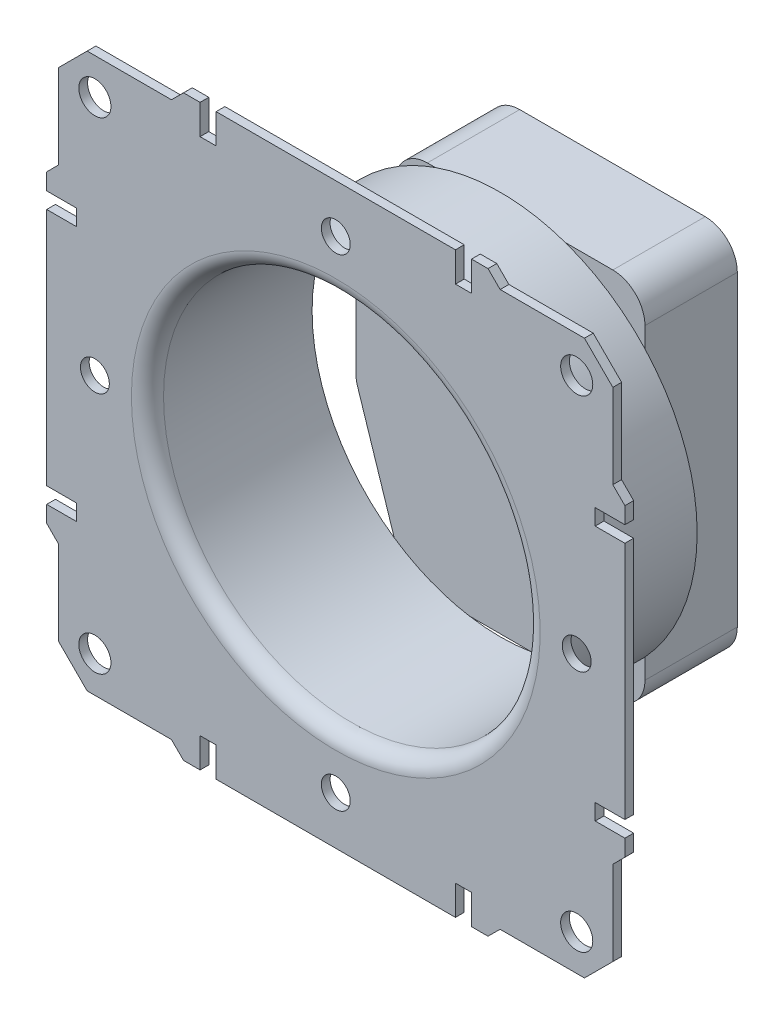
SolidWorks part; units mm, degrees
ref_plane "Спереди" through (0, 0, 0) normal (0, 0, 1) x (1, 0, 0)
ref_plane "Сверху" through (0, 0, 0) normal (0, 1, 0) x (1, 0, 0)
ref_plane "Справа" through (0, 0, 0) normal (1, 0, 0) x (0, 0, -1)
sketch "Эскиз1" plane through (0, 0, 0) normal (0, 0, 1) x (1, 0, 0)
  line L0 (-34.5, -34.5) -> (34.5, 34.5) construction
  line L1 (-34.5, -34.5) -> (34.5, -34.5) construction
  line L2 (-34.5, -34.5) -> (-34.5, 34.5) construction
  line L3 (-34.5, 34.5) -> (34.5, 34.5) construction
  line L4 (34.5, -34.5) -> (34.5, 34.5) construction
  line L5 (-30.9645, 34.5) -> (-34.5, 30.9645)
  line L6 (-34.5, 30.9645) -> (-34.5, 20.4645)
  line L7 (0, 0) -> (-34.5, 0) construction
  line L8 (-34.5, 20.4645) -> (-36, 18.9563)
  line L9 (-36, 18.9563) -> (-36, 16.901)
  line L10 (-36, 16.901) -> (-32.3, 16.901)
  line L11 (-32.3, 16.901) -> (-32.3, 14.901)
  line L12 (-32.3, 14.901) -> (-36, 14.901)
  line L13 (-36, 14.901) -> (-36, -14.901)
  line L14 (-32.3, -14.901) -> (-36, -14.901)
  line L15 (-32.3, -16.901) -> (-32.3, -14.901)
  line L16 (-36, -16.901) -> (-32.3, -16.901)
  line L17 (-36, -18.9563) -> (-36, -16.901)
  line L18 (-34.5, -20.4645) -> (-36, -18.9563)
  line L19 (-34.5, -30.9645) -> (-34.5, -20.4645)
  line L20 (34.5, 30.9645) -> (30.9645, 34.5)
  line L21 (30.9645, 34.5) -> (20.4645, 34.5)
  line L22 (20.4645, 34.5) -> (18.9563, 36)
  line L23 (18.9563, 36) -> (16.901, 36)
  line L24 (16.901, 36) -> (16.901, 32.3)
  line L25 (16.901, 32.3) -> (14.901, 32.3)
  line L26 (14.901, 32.3) -> (14.901, 36)
  line L27 (14.901, 36) -> (-14.901, 36)
  line L28 (-14.901, 32.3) -> (-14.901, 36)
  line L29 (-16.901, 32.3) -> (-14.901, 32.3)
  line L30 (-16.901, 36) -> (-16.901, 32.3)
  line L31 (-18.9563, 36) -> (-16.901, 36)
  line L32 (-20.4645, 34.5) -> (-18.9563, 36)
  line L33 (-30.9645, 34.5) -> (-20.4645, 34.5)
  line L34 (30.9645, -34.5) -> (34.5, -30.9645)
  line L35 (34.5, -30.9645) -> (34.5, -20.4645)
  line L36 (34.5, -20.4645) -> (36, -18.9563)
  line L37 (36, -18.9563) -> (36, -16.901)
  line L38 (36, -16.901) -> (32.3, -16.901)
  line L39 (32.3, -16.901) -> (32.3, -14.901)
  line L40 (32.3, -14.901) -> (36, -14.901)
  line L41 (36, -14.901) -> (36, 14.901)
  line L42 (32.3, 14.901) -> (36, 14.901)
  line L43 (32.3, 16.901) -> (32.3, 14.901)
  line L44 (36, 16.901) -> (32.3, 16.901)
  line L45 (36, 18.9563) -> (36, 16.901)
  line L46 (34.5, 20.4645) -> (36, 18.9563)
  line L47 (34.5, 30.9645) -> (34.5, 20.4645)
  line L48 (-34.5, -30.9645) -> (-30.9645, -34.5)
  line L49 (-30.9645, -34.5) -> (-20.4645, -34.5)
  line L50 (-20.4645, -34.5) -> (-18.9563, -36)
  line L51 (-18.9563, -36) -> (-16.901, -36)
  line L52 (-16.901, -36) -> (-16.901, -32.3)
  line L53 (-16.901, -32.3) -> (-14.901, -32.3)
  line L54 (-14.901, -32.3) -> (-14.901, -36)
  line L55 (-14.901, -36) -> (14.901, -36)
  line L56 (14.901, -32.3) -> (14.901, -36)
  line L57 (16.901, -32.3) -> (14.901, -32.3)
  line L58 (16.901, -36) -> (16.901, -32.3)
  line L59 (18.9563, -36) -> (16.901, -36)
  line L60 (20.4645, -34.5) -> (18.9563, -36)
  line L61 (30.9645, -34.5) -> (20.4645, -34.5)
  circle A0 centre (-30, 30) radius 2
  circle A1 centre (-30, 0) radius 1.8
  circle A2 centre (30, 30) radius 2
  circle A3 centre (0, 30) radius 1.8
  circle A4 centre (30, -30) radius 2
  circle A5 centre (30, 0) radius 1.8
  circle A6 centre (-30, -30) radius 2
  circle A7 centre (0, -30) radius 1.8
  circle A8 centre (0, 0) radius 23.45
  point P5 (0, 0)
  point P21 (-36, 0)
  point P44 (0, 36)
  point P64 (36, 0)
  point P84 (0, -36)
  point P92 (0, 0)
  dimension "D8" = 4
  dimension "D13" = 3.6
  dimension "D16" = 46.9
  dimension "D1" = 69
  dimension "D2" = 69
  dimension "D3" = 5
  dimension "D4" = 45
  dimension "D5" = 10.5
  dimension "D6" = 4.5
  dimension "D7" = 4.5
  dimension "D9" = 1.5
  dimension "D10" = 17.599
  dimension "D11" = 3.7
  dimension "D12" = 2
  dimension "D14" = 6
  dimension "D17" = 72
  dimension "D15" = 4
extrude "Бобышка-Вытянуть1" add sketch "Эскиз1" along normal blind 1.09
sketch "Эскиз2" plane through (0, 0, 1.09) normal (0, 0, 1) x (1, 0, 0)
  circle A0 centre (0, 0) radius 23.45 construction
  circle A1 centre (0, 0) radius 23.45
  circle A2 centre (0, 0) radius 24.5
  dimension "D1" = 49
extrude "Бобышка-Вытянуть2" add sketch "Эскиз2" against normal blind 20.5
fillet "Скругление1" radius 2 2 edges at (23.45, 0, 1.09) (-24.5, 0, 0)
sketch "Эскиз3" plane through (0, 0, -19.41) normal (0, 0, -1) x (-1, 0, 0)
  line L0 (0, -24.5) -> (0, 24.5) construction
  line L1 (-18, -19.125) -> (-18, 19.125)
  line L2 (0, 0) -> (18, 0) construction
  line L3 (18, -4.038) -> (18, 4.038)
  line L4 (17.804, 5.2748) -> (12.8984, 20.3619)
  line L5 (17.804, -5.2748) -> (12.8984, -20.3619)
  line L6 (9.0945, -23.125) -> (-14, -23.125)
  line L7 (-14, 23.125) -> (9.0945, 23.125)
  circle A0 centre (0, 0) radius 24.5 construction
  circle A1 centre (0, 0) radius 24.5 construction
  circle A2 centre (0, 0) radius 1.5
  arc A3 (12.8984, 20.3619) -> (9.0945, 23.125) centre (9.0945, 19.125) ccw
  arc A4 (18, 4.038) -> (17.804, 5.2748) centre (14, 4.038) ccw
  arc A5 (17.804, -5.2748) -> (18, -4.038) centre (14, -4.038) ccw
  arc A6 (12.8984, -20.3619) -> (9.0945, -23.125) centre (9.0945, -19.125) cw
  arc A7 (-14, 23.125) -> (-18, 19.125) centre (-14, 19.125) ccw
  arc A8 (-14, -23.125) -> (-18, -19.125) centre (-14, -19.125) cw
  point P11 (-18, 0)
  point P16 (18, 0)
  point P20 (12, 23.125)
  point P23 (18, 4.6719)
  point P26 (18, -4.6719)
  point P31 (-18, 23.125)
  point P34 (-18, -23.125)
  dimension "D1" = 3
  dimension "D7" = 4
  dimension "D2" = 46.25
  dimension "D3" = 18
  dimension "D4" = 18
  dimension "D6" = 6
extrude "Бобышка-Вытянуть3" add sketch "Эскиз3" along normal blind 11.5
